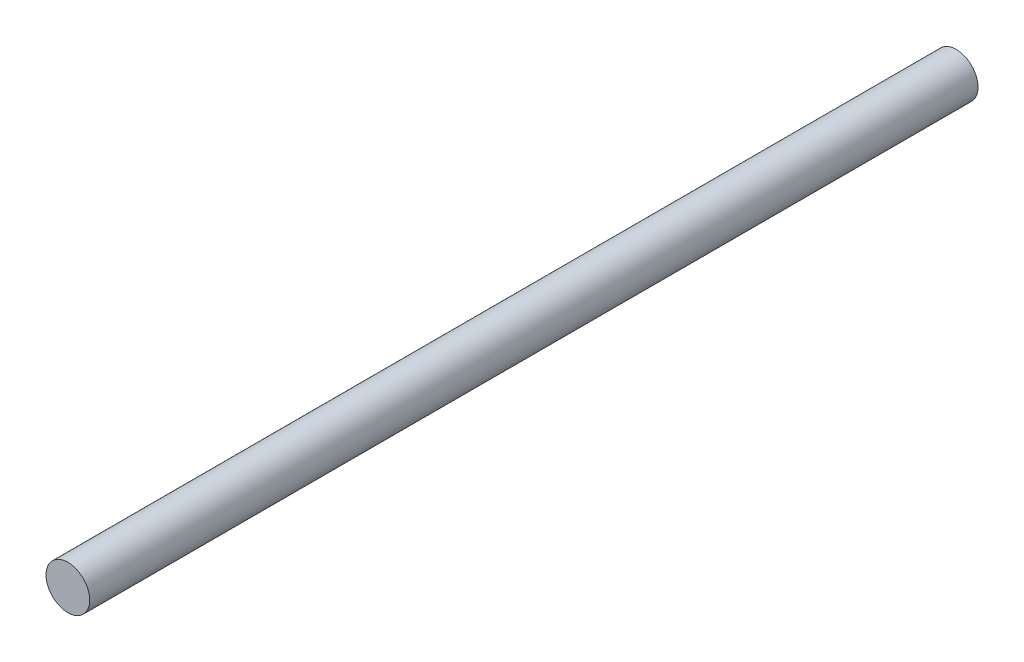
SolidWorks part; units mm, degrees
material "1060 Alloy"
ref_plane "Front Plane" through (0, 0, 0) normal (0, 0, 1) x (1, 0, 0)
ref_plane "Top Plane" through (0, 0, 0) normal (0, 1, 0) x (1, 0, 0)
ref_plane "Right Plane" through (0, 0, 0) normal (1, 0, 0) x (0, 0, -1)
sketch "Sketch1" plane through (0, 0, 0) normal (0, 0, 1) x (1, 0, 0)
  circle A0 centre (0, 0) radius 1.5
  dimension "D1" = 3
extrude "Boss-Extrude1" add sketch "Sketch1" along normal blind 61
